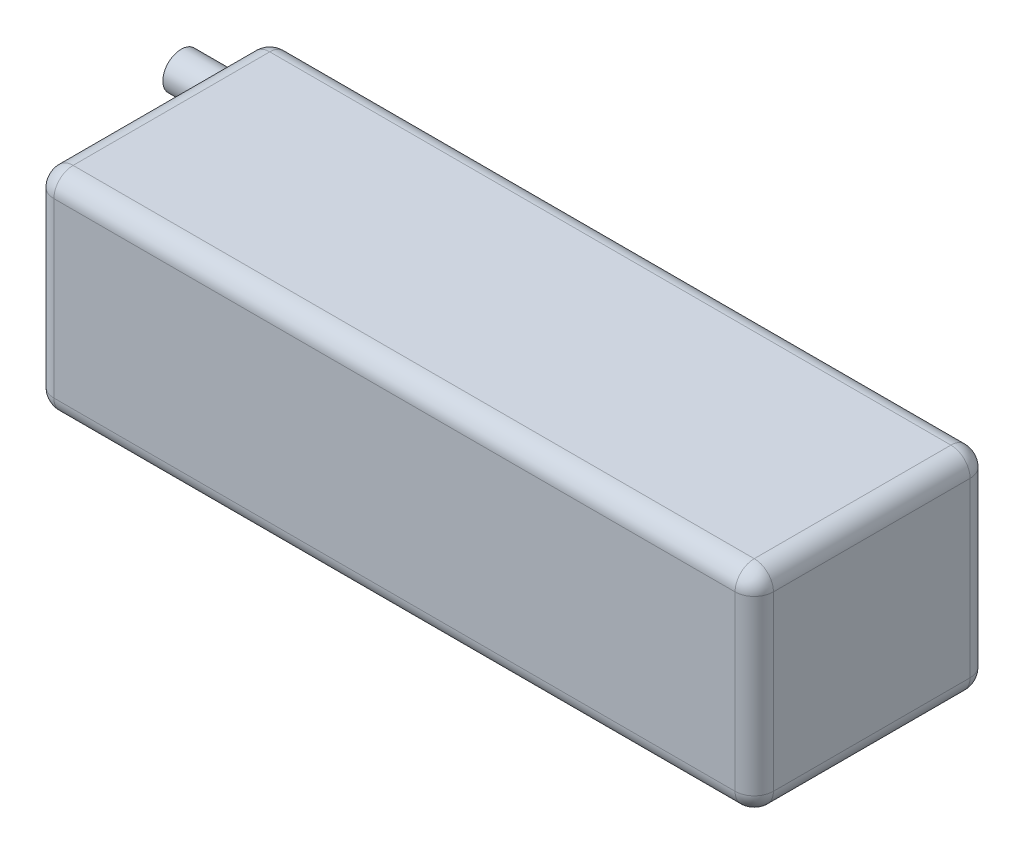
SolidWorks part; units mm, degrees
ref_plane "Front Plane" through (0, 0, 0) normal (0, 0, 1) x (1, 0, 0)
ref_plane "Top Plane" through (0, 0, 0) normal (0, 1, 0) x (1, 0, 0)
ref_plane "Right Plane" through (0, 0, 0) normal (1, 0, 0) x (0, 0, -1)
sketch "Sketch1" plane through (0, 0, 0) normal (0, 1, 0) x (1, 0, 0)
  line L1 (0, 0) -> (150, 0)
  line L2 (0, 0) -> (0, 49)
  line L3 (0, 49) -> (150, 49)
  line L4 (150, 0) -> (150, 49)
  dimension "D1" = 150
  dimension "D2" = 49
extrude "Boss-Extrude1" add sketch "Sketch1" along normal blind 44
sketch "Sketch2" plane through (0, 0, 0) normal (-1, 0, 0) x (0, 0, 1)
  circle A0 centre (-40.5294, 35.8869) radius 3.8245
  circle A1 centre (-40.5294, 8.9066) radius 3.8245
extrude "Boss-Extrude2" add sketch "Sketch2" along normal blind 10 separate body
ref_plane "Plane1" through (0, 0, -24.5) normal (0, 0, -1) x (-1, 0, 0)
ref_plane "Plane2" through (0, 22, 0) normal (0, 1, 0) x (1, 0, 0)
ref_plane "Plane3" through (75, 0, 0) normal (-1, 0, 0) x (0, 0, 1)
fillet "Fillet1" radius 4 12 edges at (150, 44, -24.5) (75, 44, 0) (150, 22, 0) (0, 44, -24.5) (0, 22, 0) (75, 0, 0) (150, 0, -24.5) (0, 0, -24.5) (150, 22, -49) (75, 44, -49) (0, 22, -49) (75, 0, -49)
